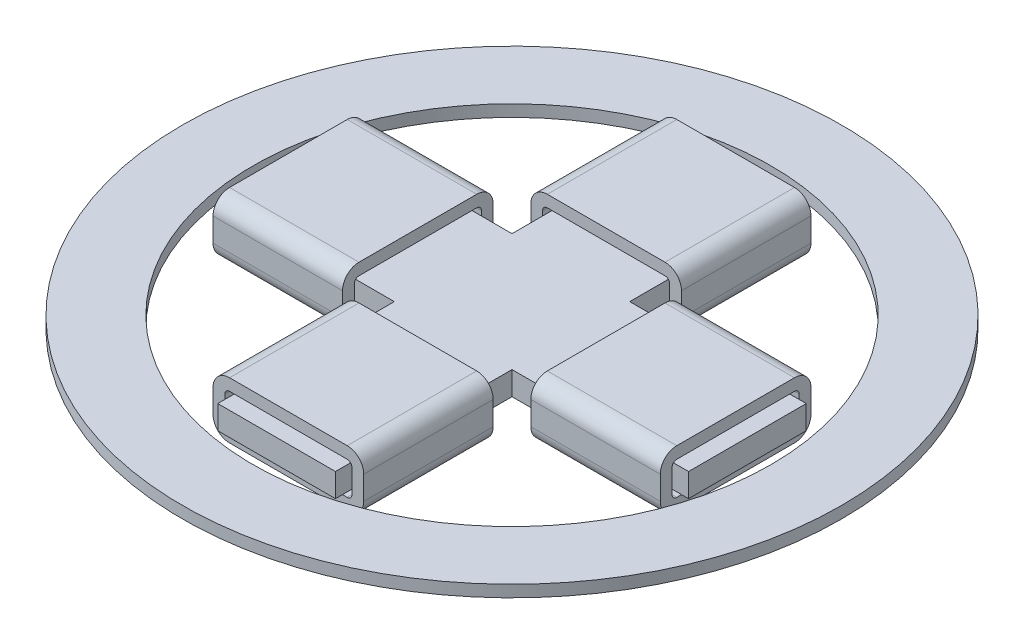
SolidWorks part; units mm, degrees
ref_plane "前视基准面" through (0, 0, 0) normal (0, 0, 1) x (1, 0, 0)
ref_plane "上视基准面" through (0, 0, 0) normal (0, 1, 0) x (1, 0, 0)
ref_plane "右视基准面" through (0, 0, 0) normal (1, 0, 0) x (0, 0, -1)
sketch "草图1" plane through (0, 0, 0) normal (0, 1, 0) x (1, 0, 0)
  line L0 (-2.5, -2.5) -> (-2.5, -10)
  line L1 (-2.5, 10) -> (2.5, 10)
  line L2 (-2.5, 10) -> (-2.5, 2.5)
  line L3 (-2.5, -10) -> (2.5, -10)
  line L4 (2.5, 10) -> (2.5, 2.5)
  line L5 (-2.5, 10) -> (2.5, -10) construction
  line L6 (-2.5, -10) -> (2.5, 10) construction
  line L7 (-10, 2.5) -> (-2.5, 2.5)
  line L8 (-10, 2.5) -> (-10, -2.5)
  line L9 (-10, -2.5) -> (-2.5, -2.5)
  line L10 (10, 2.5) -> (10, -2.5)
  line L11 (-10, 2.5) -> (10, -2.5) construction
  line L12 (-10, -2.5) -> (10, 2.5) construction
  line L14 (2.5, -2.5) -> (10, -2.5)
  line L15 (2.5, -2.5) -> (2.5, -10)
  line L16 (2.5, 2.5) -> (10, 2.5)
  point P0 (0, 0)
  point P6 (0, 0)
  dimension "D1" = 20
  dimension "D2" = 5
  dimension "D3" = 20
  dimension "D4" = 5
extrude "凸台-拉伸1" add sketch "草图1" along normal blind 1
sketch "草图2" plane through (0, 0, 0) normal (1, 0, 0) x (0, 0, -1)
  line L0 (-2.5, 1) -> (2.5, 1) construction
  line L1 (-2.5, 1.2) -> (2.5, 1.2)
  line L2 (-2.7, 1) -> (-2.7, 0)
  line L3 (-2.5, -0.2) -> (2.5, -0.2)
  line L4 (2.7, 1) -> (2.7, 0)
  line L5 (2.5, 1) -> (2.5, 0) construction
  line L6 (-2.5, 0) -> (2.5, 0) construction
  line L7 (-2.5, 1) -> (-2.5, 0) construction
  arc A0 (-2.5, -0.2) -> (-2.7, 0) centre (-2.5, 0) cw
  arc A1 (2.7, 0) -> (2.5, -0.2) centre (2.5, 0) cw
  arc A2 (2.5, 1.2) -> (2.7, 1) centre (2.5, 1) cw
  arc A3 (-2.7, 1) -> (-2.5, 1.2) centre (-2.5, 1) cw
  dimension "D5" = 0.2
  dimension "D6" = 0.2
  dimension "D7" = 0.2
  dimension "D8" = 0.2
  dimension "D1" = 0.2
  dimension "D2" = 0.2
  dimension "D3" = 0.2
  dimension "D4" = 0.2
extrude "拉伸-薄壁1" add sketch "草图2" along normal offset from surface (5.5 mm away) 0.5 from offset 4 separate body thin up to face at (10, 0.5, 0) thin type one direction wall 0.5
ref_axis "基准轴1" through (0, 0, 0) along (0, 1, 0)
pattern_circular "阵列(圆周)1" count 4 every 90 about axis through (0, 0, 0) along (0, 1, 0) of bodies 107
sketch "草图3" plane through (0, 0, 0) normal (1, 0, 0) x (0, 0, -1)
  line L1 (-9.5, 1.7) -> (-4, 1.7)
  line L2 (-9.5, 1.7) -> (-9.5, 1.2)
  line L3 (-9.5, 1.2) -> (-4, 1.2)
  line L4 (-4, 1.7) -> (-4, 1.2)
  point P10 (0, 0)
surface "曲面-基准面1" sketch "草图3"
pattern_circular "阵列(圆周)2" count 4 every 90 about axis through (0, 0, 0) along (0, 1, 0) of bodies 111
sketch "草图4" plane through (0, 0, 0) normal (0, 1, 0) x (1, 0, 0)
  circle A0 centre (0, 0) radius 12.5
  dimension "D1" = 25
extrude "拉伸-薄壁2" add sketch "草图4" along normal blind 0.5 separate body thin thin type mid plane wall 3
sketch "草图5" plane through (0, 0, 0) normal (1, 0, 0) x (0, 0, -1)
  line L1 (-14, 0.5) -> (-11, 0.5)
  line L2 (-14, 0.5) -> (-14, 0)
  line L3 (-14, 0) -> (-11, 0)
  line L4 (-11, 0.5) -> (-11, 0)
surface "曲面-基准面2" sketch "草图5"
